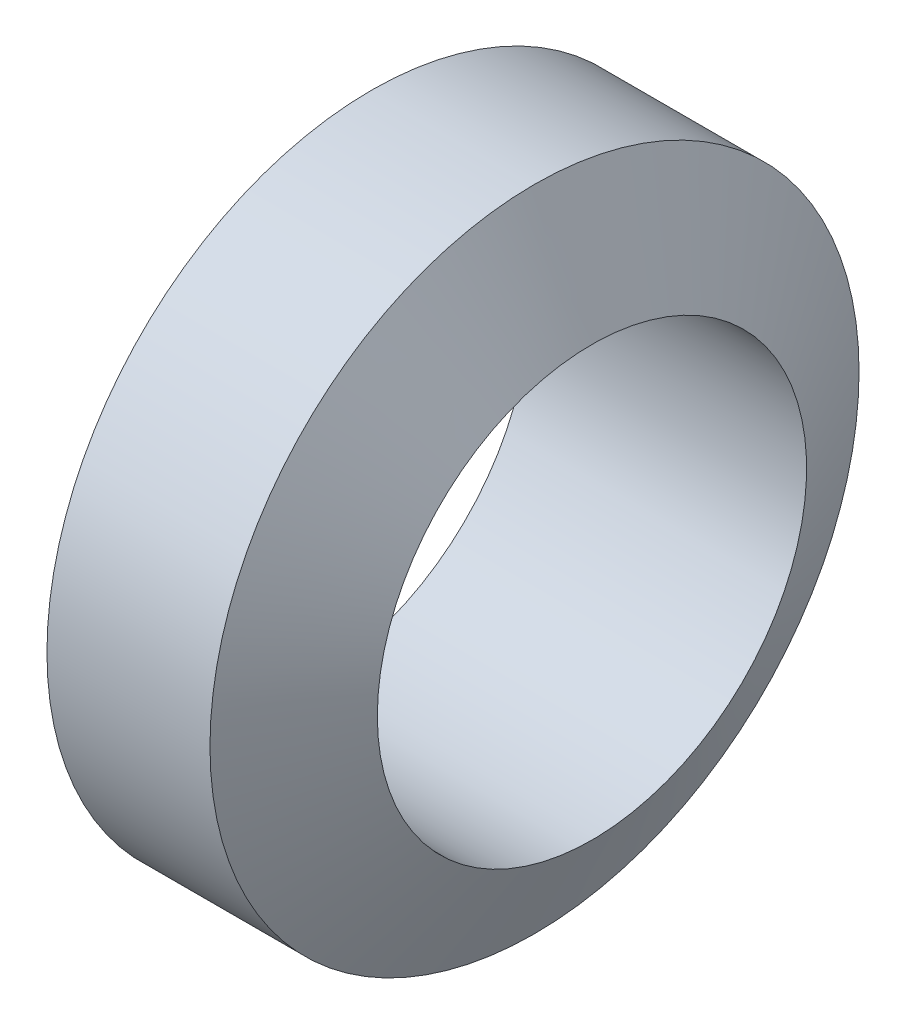
SolidWorks part; units mm, degrees
material "POM Acetal Copolymer"
ref_plane "Alzado" through (0, 0, 0) normal (0, 0, 1) x (1, 0, 0)
ref_plane "Planta" through (0, 0, 0) normal (0, 1, 0) x (1, 0, 0)
ref_plane "Vista lateral" through (0, 0, 0) normal (1, 0, 0) x (0, 0, -1)
sketch "Sketch1" plane through (0, 0, 0) normal (0, 0, 1) x (1, 0, 0)
  line L0 (0, -268.3724) -> (0, 13150.2461) construction
  line L1 (-268.3724, 0) -> (13150.2461, 0) construction
  line L2 (5.115, 0) -> (5.115, 7.9) construction
  line L3 (5.115, 7.9) -> (3, 11.945)
  line L4 (3, 11.945) -> (-3, 11.945)
  line L5 (5.115, 7.9) -> (-5.115, 7.9)
  line L6 (-5.115, 7.9) -> (-3, 11.945)
  point P11 (0, 7.9)
  point P12 (0, 11.945)
  dimension "D1" = 5.115
  dimension "D2" = 6
  dimension "D3" = 23.89
  dimension "D4" = 15.8
revolve "Revolve1" add sketch "Sketch1" angle 360 about L1
